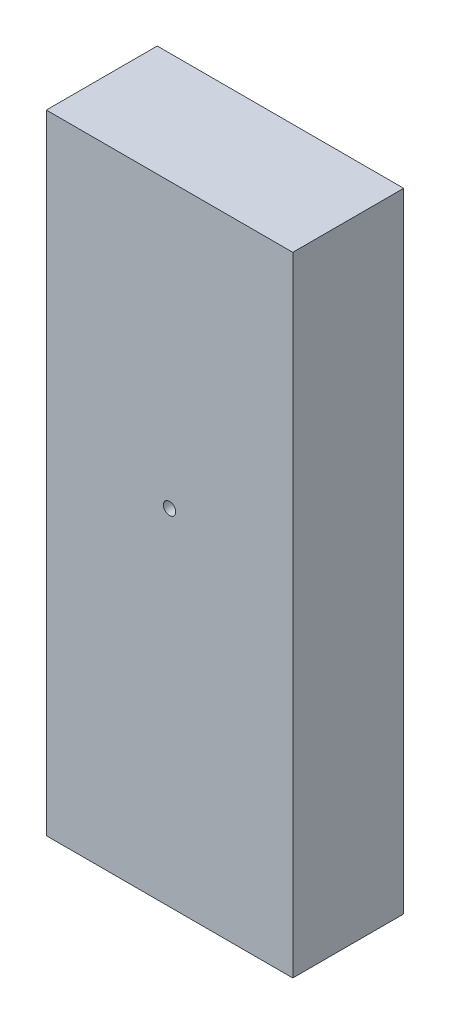
SolidWorks part; units mm, degrees
ref_plane "Plan de face" through (0, 0, 0) normal (0, 0, 1) x (1, 0, 0)
ref_plane "Plan de dessus" through (0, 0, 0) normal (0, 1, 0) x (1, 0, 0)
ref_plane "Plan de droite" through (0, 0, 0) normal (1, 0, 0) x (0, 0, -1)
sketch "Esquisse1" plane through (0, 0, 0) normal (0, 0, 1) x (1, 0, 0)
  line L1 (-15.9031, 5.0885) -> (4.0969, 5.0885)
  line L2 (-15.9031, 5.0885) -> (-15.9031, -45.9115)
  line L3 (-15.9031, -45.9115) -> (4.0969, -45.9115)
  line L4 (4.0969, 5.0885) -> (4.0969, -45.9115)
  dimension "D1" = 51
  dimension "D2" = 20
extrude "Extrusion1" add sketch "Esquisse1" along normal blind 9
sketch "Esquisse2" plane through (0, 0, 9) normal (0, 0, 1) x (1, 0, 0)
  line L0 (-15.9031, 5.0885) -> (-15.9031, -45.9115) construction
  line L1 (4.0969, 5.0885) -> (-15.9031, 5.0885) construction
  circle A0 centre (-5.9031, -17.9115) radius 0.5
  dimension "D2" = 1
  dimension "D1" = 10
  dimension "D3" = 23
extrude "Extrusion2" cut sketch "Esquisse2" against normal up to next
